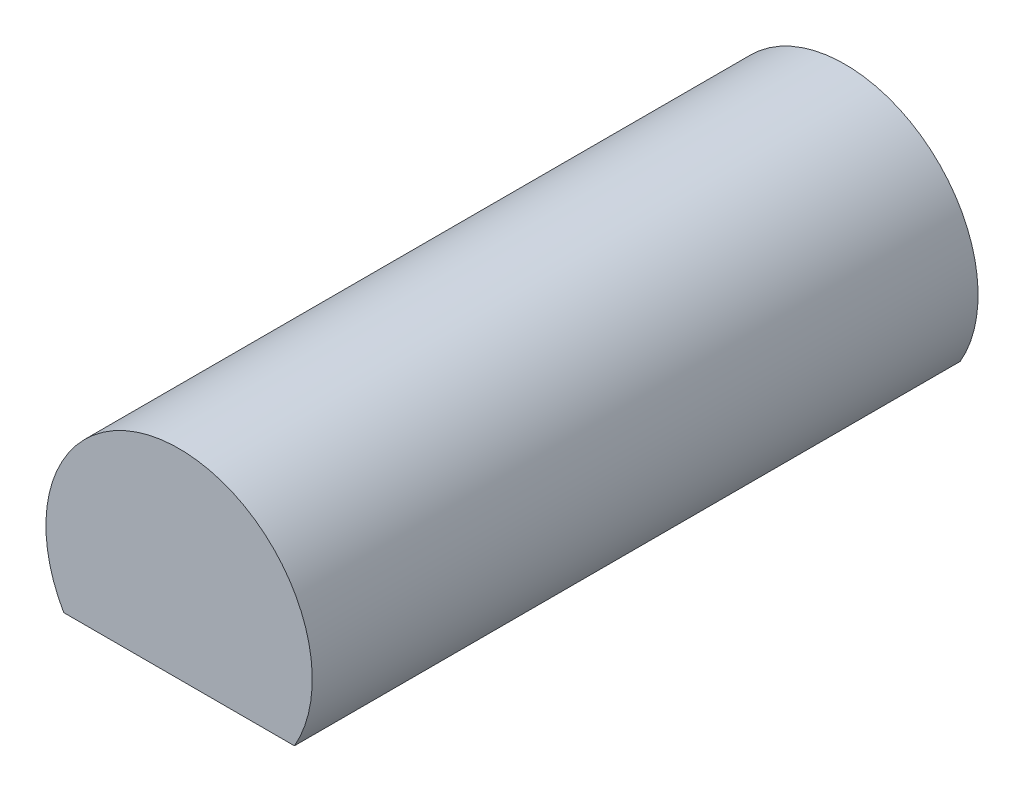
SolidWorks part; units mm, degrees
ref_plane "Front Plane" through (0, 0, 0) normal (0, 0, 1) x (1, 0, 0)
ref_plane "Top Plane" through (0, 0, 0) normal (0, 1, 0) x (1, 0, 0)
ref_plane "Right Plane" through (0, 0, 0) normal (1, 0, 0) x (0, 0, -1)
sketch "Sketch2" plane through (0, 0, 0) normal (0, 0, 1) x (1, 0, 0)
  line L1 (0, -1) -> (1.7321, -1)
  line L2 (1.7321, -1) -> (-1.7321, -1)
  arc A0 (1.7321, -1) -> (-1.7321, -1) centre (0, 0) ccw
extrude "Boss-Extrude1" add sketch "Sketch2" along normal blind 10
